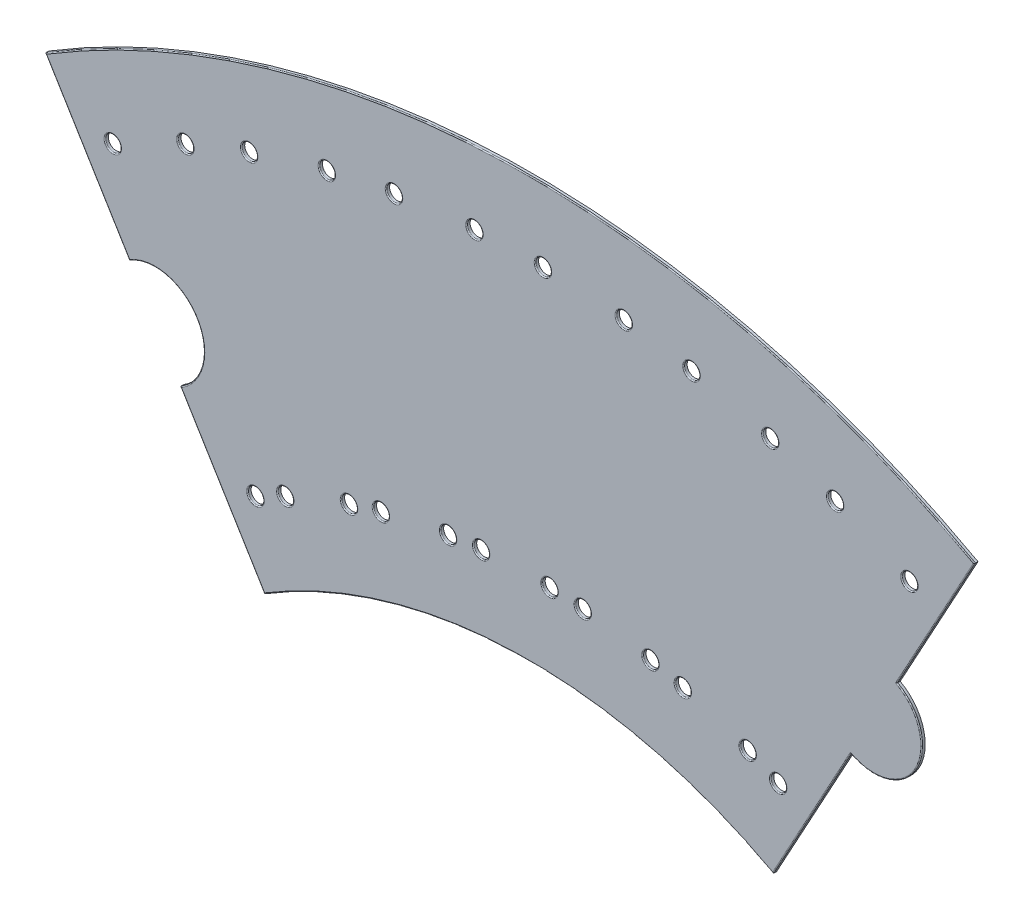
SolidWorks part; units mm, degrees
ref_plane "Front" through (0, 0, 0) normal (0, 0, 1) x (1, 0, 0)
ref_plane "Top" through (0, 0, 0) normal (0, 1, 0) x (1, 0, 0)
ref_plane "Right" through (0, 0, 0) normal (1, 0, 0) x (0, 0, -1)
sketch "Sketch1" plane through (0, 0, 0) normal (0, 0, 1) x (1, 0, 0)
  line L0 (0, 0) -> (-98.943, 162.2044)
  line L1 (0, 0) -> (91.0016, 166.7894)
  line L2 (-76.5507, 125.495) -> (-111.4935, 104.1803)
  circle A0 centre (0, 0) radius 190
  circle A1 centre (-85.1558, 153.0441) radius 1.6
  circle A2 centre (0, 0) radius 104
  circle A3 centre (0, 0) radius 147
  circle A4 centre (-55.9936, 105.2365) radius 1.6
  circle A5 centre (-97.1077, 145.7535) radius 1.6
  circle A6 centre (-67.9455, 97.9459) radius 1.6
  circle A7 centre (-57.2862, 165.5062) radius 1.6
  circle A8 centre (-70.3226, 160.4018) radius 1.6
  circle A9 centre (-49.9052, 108.2565) radius 1.6
  circle A10 centre (-36.8688, 113.3609) radius 1.6
  circle A11 centre (-27.6761, 172.9394) radius 1.6
  circle A12 centre (-41.4007, 170.1763) radius 1.6
  circle A13 centre (-30.3484, 115.2778) radius 1.6
  circle A14 centre (-16.6238, 118.0409) radius 1.6
  circle A15 centre (2.775, 175.118) radius 1.6
  circle A16 centre (-11.221, 174.7801) radius 1.6
  circle A17 centre (-9.8696, 118.7964) radius 1.6
  circle A18 centre (4.1263, 119.1343) radius 1.6
  circle A19 centre (33.1417, 171.9757) radius 1.6
  circle A20 centre (19.2998, 174.0733) radius 1.6
  circle A21 centre (10.9091, 118.7055) radius 1.6
  circle A22 centre (24.7511, 116.6078) radius 1.6
  circle A23 centre (62.5015, 163.608) radius 1.6
  circle A24 centre (49.2341, 168.0774) radius 1.6
  circle A25 centre (31.3564, 115.0077) radius 1.6
  circle A26 centre (44.6238, 110.5383) radius 1.6
  circle A27 centre (89.9622, 150.2691) radius 1.6
  circle A28 centre (77.6724, 156.9745) radius 1.6
  circle A29 centre (50.8509, 107.8155) radius 1.6
  circle A30 centre (63.1406, 101.1101) radius 1.6
  point P67 (0, 0)
  dimension "D1" = 380
  dimension "D3" = 86
  dimension "D5" = 3.2
  dimension "D7" = 43
  dimension "D2" = 60
  dimension "D4" = 7
  dimension "D6" = 28
  dimension "D8" = 7
extrude "Boss-Extrude1" add sketch "Sketch1" along normal blind 0.7 contours A3 L1 A0 L0 A24 A23 A16 A15 A8 A7 A1 A11 A12 A19 A20 A28 | L1 A3 L0 A2 A29 A22 A21 A14 A13 A4 A9 A10 A17 A18 A25 A26
sketch "Sketch2" plane through (0, 0, 0.7) normal (0, 0, 1) x (1, 0, 0)
  line L0 (-54.1583, 88.7856) -> (-98.943, 162.2044) construction
  circle A0 centre (-76.5507, 125.495) radius 10
  dimension "D1" = 20
extrude "Cut-Extrude1" cut sketch "Sketch2" against normal through all
sketch "Sketch3" plane through (0, 0, 0) normal (0, 0, 1) x (1, 0, 0)
  line L0 (49.8114, 91.2952) -> (91.0016, 166.7894) construction
  circle A0 centre (70.4065, 129.0423) radius 9.8
  dimension "D1" = 19.6
extrude "Boss-Extrude2" add sketch "Sketch3" along normal blind 0.7
fillet "Fillet1" radius 0.2 32 edges at (50.8341, 168.0774, 0.7) (64.1015, 163.608, 0.7) (-9.621, 174.7801, 0.7) (4.375, 175.118, 0.7) (-68.7226, 160.4018, 0.7) (-55.6862, 165.5062, 0.7) (-83.5558, 153.0441, 0.7) (-26.0761, 172.9394, 0.7) (-39.8007, 170.1763, 0.7) (34.7417, 171.9757, 0.7) (20.8998, 174.0733, 0.7) (79.2724, 156.9745, 0.7) (52.4509, 107.8155, 0.7) (26.3511, 116.6078, 0.7) (12.5091, 118.7055, 0.7) (-15.0238, 118.0409, 0.7) (-28.7484, 115.2778, 0.7) (-54.3936, 105.2365, 0.7) (-48.3052, 108.2565, 0.7) (-35.2688, 113.3609, 0.7) (-8.2696, 118.7964, 0.7) (5.7263, 119.1343, 0.7) (32.9564, 115.0077, 0.7) (46.2238, 110.5383, 0.7) (-2.5097, 103.9697, 0.7) (-62.7507, 102.8718, 0.7) (-68.0136, 130.7025, 0.7) (-90.3506, 148.1183, 0.7) (-4.585, 189.9447, 0.7) (83.051, 152.2173, 0.7) (79.0094, 124.3485, 0.7) (57.7621, 105.8674, 0.7)
